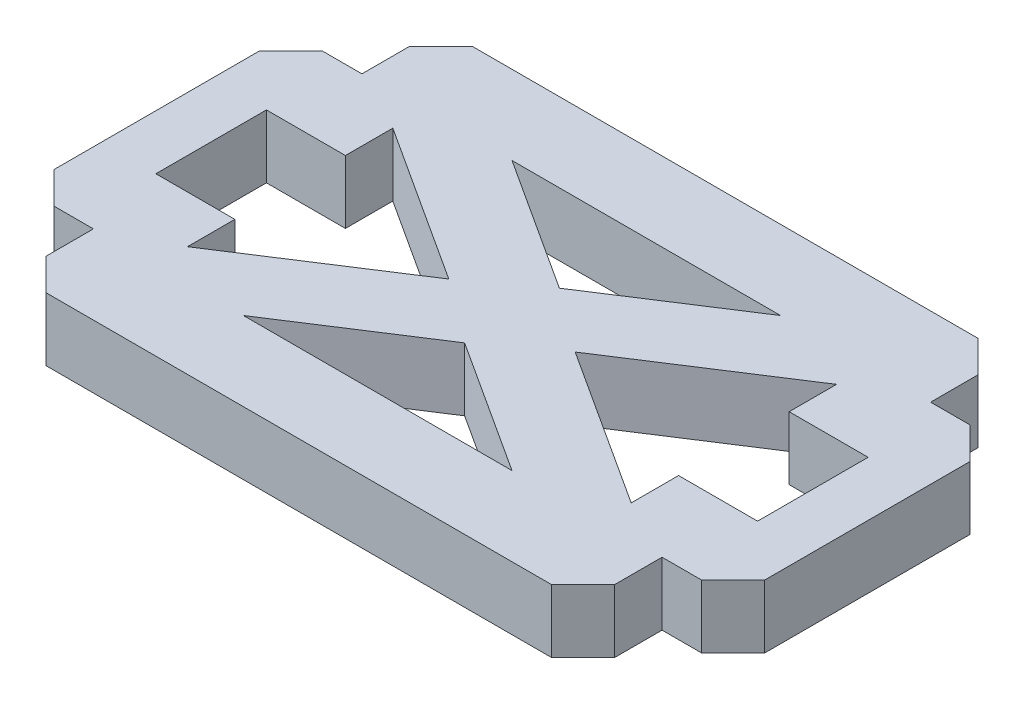
SolidWorks part; units mm, degrees
ref_plane "前视基准面" through (0, 0, 0) normal (0, 0, 1) x (1, 0, 0)
ref_plane "上视基准面" through (0, 0, 0) normal (0, 1, 0) x (1, 0, 0)
ref_plane "右视基准面" through (0, 0, 0) normal (1, 0, 0) x (0, 0, -1)
sketch "草图1" plane through (0, 0, 0) normal (0, 1, 0) x (1, 0, 0)
  line L0 (-18, 13.5) -> (-18, 8.5)
  line L1 (-18, 13.5) -> (18, 13.5)
  line L2 (-22.5, 8.5) -> (-22.5, -8.5)
  line L3 (-18, -13.5) -> (18, -13.5)
  line L4 (22.5, 8.5) -> (22.5, -8.5)
  line L5 (18, 8.5) -> (22.5, 8.5)
  line L6 (18, 13.5) -> (18, 8.5)
  line L7 (-18, 8.5) -> (-22.5, 8.5)
  line L8 (0, -0.1153) -> (0, 49999.8847) construction
  line L9 (0, 0) -> (50000, 0) construction
  line L10 (-18, -13.5) -> (-18, -8.5)
  line L11 (-18, -8.5) -> (-22.5, -8.5)
  line L12 (18, -8.5) -> (22.5, -8.5)
  line L13 (18, -13.5) -> (18, -8.5)
  point P0 (0, 0)
  dimension "D1" = 45
  dimension "D2" = 36
  dimension "D3" = 17
  dimension "D4" = 5
extrude "凸台-拉伸1" add sketch "草图1" along normal mid plane 4
sketch "草图2" plane through (0, 2, 0) normal (0, 1, 0) x (1, 0, 0)
  line L0 (0, 0) -> (0, 50000) construction
  line L1 (0, 0) -> (50000, 0) construction
  line L2 (0, 3) -> (8.5, 8.5)
  line L3 (8.5, 8.5) -> (-8.5, 8.5)
  line L4 (4, 0) -> (14.0455, 6.5)
  line L5 (14.0455, 6.5) -> (14.0455, 3.5)
  line L6 (14.0455, 3.5) -> (19.0455, 3.5)
  line L7 (19.0455, 3.5) -> (19.0455, -3.5)
  line L8 (22.5, 8.5) -> (18, 8.5) construction
  line L9 (14.0455, -3.5) -> (19.0455, -3.5)
  line L10 (14.0455, -6.5) -> (14.0455, -3.5)
  line L11 (4, 0) -> (14.0455, -6.5)
  line L12 (8.5, -8.5) -> (-8.5, -8.5)
  line L13 (0, -3) -> (8.5, -8.5)
  line L14 (0, -3) -> (-8.5, -8.5)
  line L15 (-4, 0) -> (-14.0455, -6.5)
  line L16 (-14.0455, -6.5) -> (-14.0455, -3.5)
  line L17 (-14.0455, -3.5) -> (-19.0455, -3.5)
  line L18 (-19.0455, 3.5) -> (-19.0455, -3.5)
  line L19 (-14.0455, 3.5) -> (-19.0455, 3.5)
  line L20 (-14.0455, 6.5) -> (-14.0455, 3.5)
  line L21 (-4, 0) -> (-14.0455, 6.5)
  line L22 (0, 3) -> (-8.5, 8.5)
  point P7 (-19.0455, 0)
  point P16 (19.0455, 0)
  point P22 (0, -8.5)
  point P30 (0, 8.5)
  dimension "D1" = 3
  dimension "D2" = 4
  dimension "D3" = 3
  dimension "D4" = 5
  dimension "D5" = 17
  dimension "D6" = 5
extrude "切除-拉伸1" cut sketch "草图2" against normal through all both and the other way through all
chamfer "倒角1" distance 2 angle 45 8 edges at (-18, 0, -13.5) (-22.5, 0, -8.5) (-22.5, 0, 8.5) (-18, 0, 13.5) (18, 0, -13.5) (22.5, 0, -8.5) (22.5, 0, 8.5) (18, 0, 13.5)
